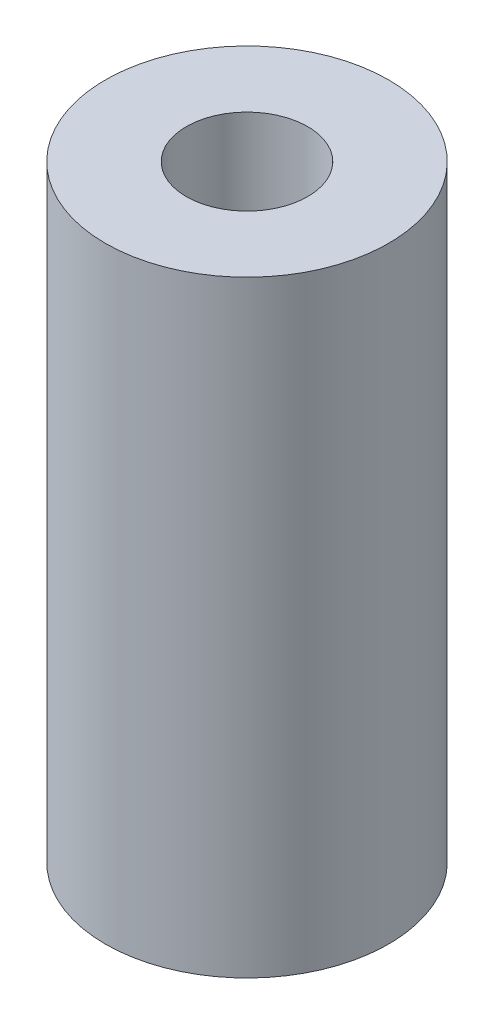
SolidWorks part; units mm, degrees
ref_plane "Front Plane" through (0, 0, 0) normal (0, 0, 1) x (1, 0, 0)
ref_plane "Top Plane" through (0, 0, 0) normal (0, 1, 0) x (1, 0, 0)
ref_plane "Right Plane" through (0, 0, 0) normal (1, 0, 0) x (0, 0, -1)
sketch "Sketch1" plane through (0, 0, 0) normal (0, 1, 0) x (1, 0, 0)
  circle A0 centre (0, 0) radius 3.5
  circle A1 centre (0, 0) radius 1.5
  dimension "D1" = 3
  dimension "D2" = 7
extrude "Boss-Extrude1" add sketch "Sketch1" along normal blind 15
